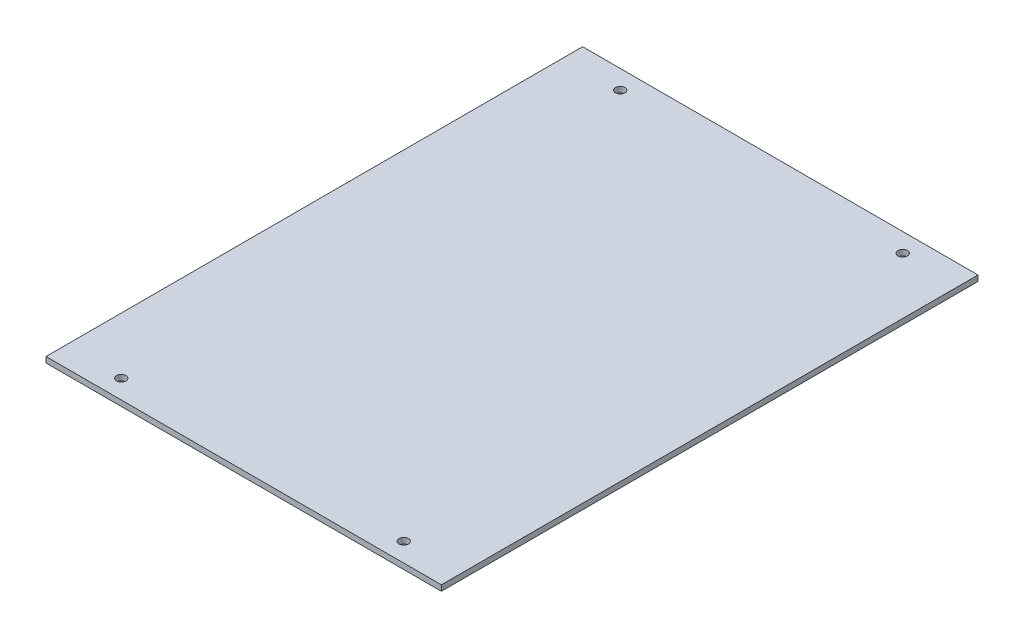
SolidWorks part; units mm, degrees
ref_plane "Front Plane" through (0, 0, 0) normal (0, 0, 1) x (1, 0, 0)
ref_plane "Top Plane" through (0, 0, 0) normal (0, 1, 0) x (1, 0, 0)
ref_plane "Right Plane" through (0, 0, 0) normal (1, 0, 0) x (0, 0, -1)
sketch "Sketch1" plane through (0, 0, 0) normal (0, 1, 0) x (1, 0, 0)
  line L0 (0, 157.7741) -> (0, -251.8153) construction
  line L1 (-105, 142.5) -> (105, 142.5)
  line L2 (-105, 142.5) -> (-105, -142.5)
  line L3 (-105, -142.5) -> (105, -142.5)
  line L4 (105, 142.5) -> (105, -142.5)
  line L5 (-105, 142.5) -> (105, -142.5) construction
  line L6 (-105, -142.5) -> (105, 142.5) construction
  line L7 (-148.9444, 0) -> (151.1443, 0) construction
  circle A0 centre (-75, 132.5) radius 2.5
  circle A1 centre (-75, -132.5) radius 2.5
  circle A2 centre (75, -132.5) radius 2.5
  circle A3 centre (75, 132.5) radius 2.5
  point P0 (0, 0)
  dimension "D3" = 5
  dimension "D4" = 30
  dimension "D5" = 10
  dimension "D1" = 285
  dimension "D2" = 210
extrude "Boss-Extrude1" add sketch "Sketch1" along normal blind 3
